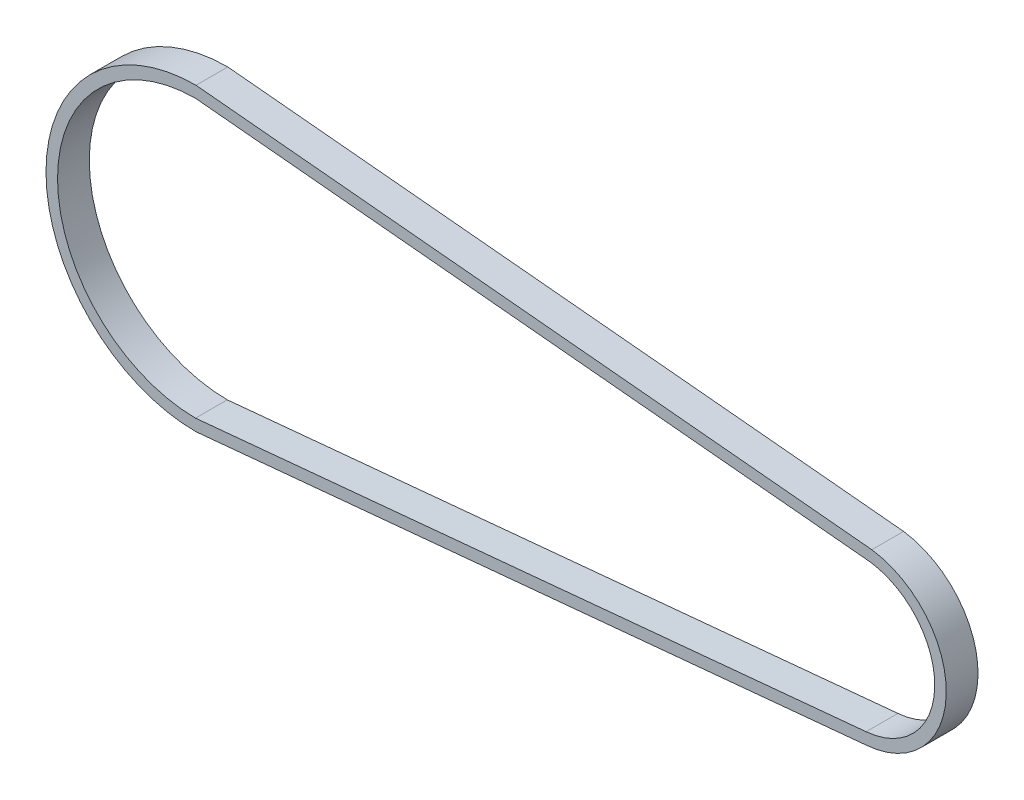
SolidWorks part; units mm, degrees
ref_plane "Plan de face" through (0, 0, 0) normal (0, 0, 1) x (1, 0, 0)
ref_plane "Plan de dessus" through (0, 0, 0) normal (0, 1, 0) x (1, 0, 0)
ref_plane "Plan de droite" through (0, 0, 0) normal (1, 0, 0) x (0, 0, -1)
sketch "Esquisse1" plane through (0, 0, 0) normal (0, 0, 1) x (1, 0, 0)
  line L0 (0, 0) -> (115, 0) construction
  line L1 (0, -26) -> (116.2968, -14.9438)
  line L2 (0, 26) -> (117.0989, 14.8524)
  line L3 (-0.093, -23.9998) -> (116.116, -12.952)
  line L4 (-0.0931, 23.9998) -> (116.8625, 12.8659)
  arc A0 (0, 26) -> (0, -26) centre (0, 0) ccw
  arc A1 (116.2968, -14.9438) -> (117.0989, 14.8524) centre (115, 0) ccw
  arc A2 (116.116, -12.952) -> (116.8625, 12.8659) centre (115, 0) ccw
  arc A3 (-0.0931, 23.9998) -> (-0.093, -23.9998) centre (0, 0) ccw
  dimension "D1" = 52
  dimension "D2" = 30
  dimension "D3" = 115
  dimension "D4" = 2
extrude "Boss.-Extru.1" add sketch "Esquisse1" along normal blind 5.5
